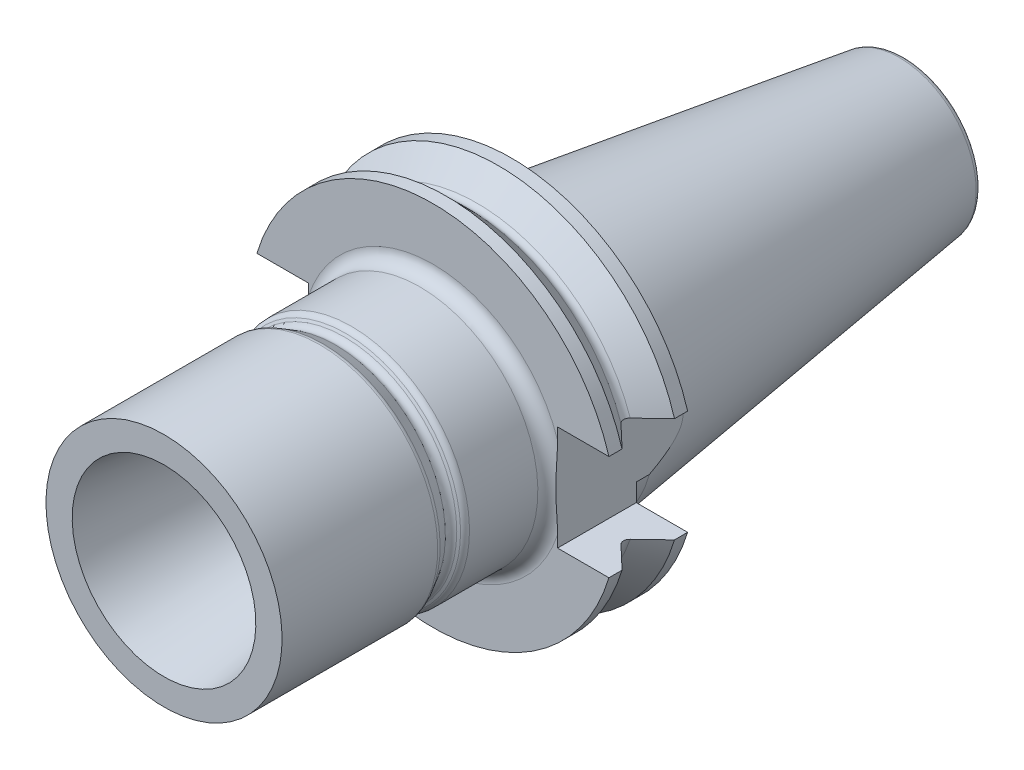
SolidWorks part; units mm, degrees
material "Alloy Steel (SS)"
ref_plane "Front Plane" through (0, 0, 0) normal (0, 0, 1) x (1, 0, 0)
ref_plane "Top Plane" through (0, 0, 0) normal (0, 1, 0) x (1, 0, 0)
ref_plane "Right Plane" through (0, 0, 0) normal (1, 0, 0) x (0, 0, -1)
sketch "Sketch1" plane through (0, 0, 0) normal (1, 0, 0) x (0, 0, -1)
  line L0 (0, 10) -> (0, 14)
  line L1 (1, 9.8595) -> (29.5696, 5.8443)
  line L2 (30, 5.3491) -> (30, 4)
  line L3 (30, 4) -> (28.5, 4)
  line L4 (28.5, 4) -> (28.5, 0)
  line L5 (28.5, 0) -> (9, 0)
  line L6 (7.7071, 1.2929) -> (3.5, 5.5)
  line L7 (3.5, 5.5) -> (-15.8269, 5.5)
  line L8 (0, 14) -> (-1, 14)
  line L9 (-1, 14) -> (-2.6464, 12.3536)
  line L10 (-3.3536, 12.3536) -> (-5, 14)
  line L11 (-5, 14) -> (-6, 14)
  line L12 (-6, 14) -> (-6, 10)
  line L13 (-7, 9) -> (-12.2113, 9)
  line L14 (-26.5, 9) -> (-26.5, 7)
  line L15 (-26.5, 7) -> (-15.8269, 5.5)
  line L16 (-14.384, 8.933) -> (-13.433, 8.384)
  line L17 (-12.75, 8.567) -> (-12.6443, 8.75)
  line L18 (-14.634, 9) -> (-26.5, 9)
  line L21 (8, 0.5858) -> (8, 0)
  line L22 (8, 0) -> (9, 0)
  line L25 (1, 9.8595) -> (0, 9.8595)
  line L26 (0, 10) -> (0, 9.8595)
  arc A0 (-3.3536, 12.3536) -> (-2.6464, 12.3536) centre (-3, 12.7071) ccw
  arc A1 (30, 5.3491) -> (29.5696, 5.8443) centre (29.5, 5.3491) ccw
  arc A2 (-12.6443, 8.75) -> (-12.2113, 9) centre (-12.2113, 8.5) cw
  arc A3 (-14.384, 8.933) -> (-14.634, 9) centre (-14.634, 8.5) ccw
  arc A4 (-13.433, 8.384) -> (-12.75, 8.567) centre (-13.183, 8.817) ccw
  arc A5 (-6, 10) -> (-7, 9) centre (-7, 10) cw
  arc A6 (8, 0.5858) -> (7.7071, 1.2929) centre (7, 0.5858) ccw
  point P24 (30, 5.7838)
  point P27 (-12.5, 9)
  point P30 (-14.5, 9)
  dimension "D18" = 0.5
  dimension "D22" = 0.5
  dimension "D23" = 1
  dimension "D26" = 1
  dimension "D2" = 14
  dimension "D3" = 30
  dimension "D4" = 82
  dimension "D5" = 1.5
  dimension "D6" = 4
  dimension "D7" = 135
  dimension "D8" = 8
  dimension "D9" = 1
  dimension "D10" = 135
  dimension "D11" = 1
  dimension "D12" = 30
  dimension "D13" = 6
  dimension "D14" = 9
  dimension "D15" = 7
  dimension "D16" = 25
  dimension "D17" = 5.5
  dimension "D19" = 30
  dimension "D20" = 12
  dimension "D21" = 14
  dimension "D24" = 10
  dimension "D25" = 20.5
revolve "Revolve1" add sketch "Sketch1" angle 360 about L5
cosmetic thread "Cosmetic Thread1" parameters "D1"=11.8659, "D2"=16.344
hole_wizard "M6 Tapped Hole1" positions "Sketch3" profile "Sketch4" tap size "M6" standard "DIN"
sketch "Sketch3" plane through (0, 0, -28.5) normal (0, 0, -1) x (-1, 0, 0)
  point P0 (0, 0)
sketch "Sketch4" plane through (0, 0, -28.5) normal (1, 0, 0) x (0, 1, 0)
  line L0 (0, 0) -> (0, 15)
  line L1 (0, 15) -> (2.5, 13.4978)
  line L2 (2.5, 13.4978) -> (2.5, 0)
  line L5 (2.5, 0) -> (0, 0)
  line L10 (0, 15) -> (-2.5, 13.4978) construction
  line L11 (0, -6.35) -> (0, 107.95) construction
  dimension "Tap Drill Dia." = 5
  dimension "Tap Drill Depth" = 15
  dimension "Drill Angle" = 118
cosmetic thread "Hole Thread1" parameters "D1"=10, "D2"=6
ref_plane "Plane2" through (9.5, 0, 0) normal (1, 0, 0) x (0, 0, -1)
sketch "Sketch5" plane through (9.5, 0, 0) normal (1, 0, 0) x (0, 0, -1)
  line L0 (-2.6464, 12.3536) -> (-2.6464, -12.3536) construction
  line L6 (-15.5531, 4) -> (10.2602, 4)
  line L8 (-15.5531, 4) -> (-15.5531, -4)
  line L9 (-15.5531, -4) -> (10.2602, -4)
  line L10 (10.2602, 4) -> (10.2602, -4)
  line L11 (-15.5531, 4) -> (10.2602, -4) construction
  line L12 (-15.5531, -4) -> (10.2602, 4) construction
  point P0 (-2.6464, 0)
  point P1 (-2.6464, 0)
  dimension "D1" = 8
extrude "Cut-Extrude1" cut sketch "Sketch5" along normal through all
mirror "Mirror1" about plane through (0, 0, 0) normal (1, 0, 0) of "Cut-Extrude1"
